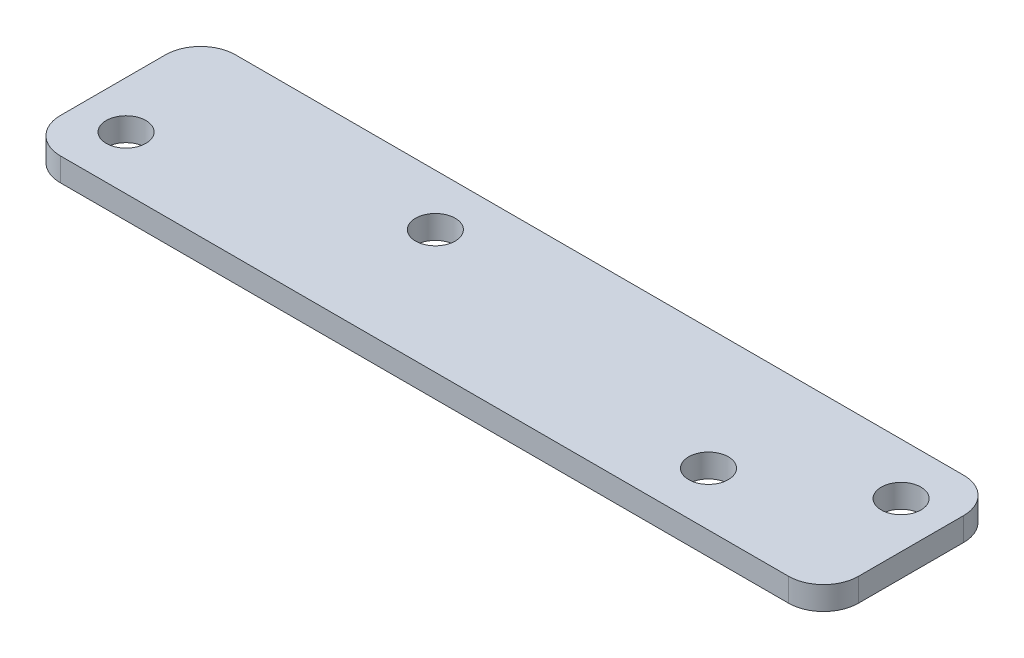
SolidWorks part; units mm, degrees
ref_plane "前视基准面" through (0, 0, 0) normal (0, 0, 1) x (1, 0, 0)
ref_plane "上视基准面" through (0, 0, 0) normal (0, 1, 0) x (1, 0, 0)
ref_plane "右视基准面" through (0, 0, 0) normal (1, 0, 0) x (0, 0, -1)
other "Configuration Table"
sketch "草图1" plane through (0, 0, 0) normal (0, 1, 0) x (1, 0, 0)
  line L1 (-107.5574, -1.3464) -> (-45.1803, -1.3464)
  line L2 (-110.5574, -4.3464) -> (-110.5574, -13.3464)
  line L3 (-107.5574, -16.3464) -> (-45.1803, -16.3464)
  line L4 (-42.1803, -4.3464) -> (-42.1803, -13.3464)
  circle A0 centre (-86.0228, -5.7574) radius 1.7
  circle A1 centre (-46.1228, -5.7574) radius 1.7
  circle A2 centre (-106.5228, -11.7574) radius 1.7
  circle A3 centre (-56.6228, -11.7574) radius 1.7
  arc A4 (-45.1803, -16.3464) -> (-42.1803, -13.3464) centre (-45.1803, -13.3464) ccw
  arc A5 (-45.1803, -1.3464) -> (-42.1803, -4.3464) centre (-45.1803, -4.3464) cw
  arc A6 (-110.5574, -13.3464) -> (-107.5574, -16.3464) centre (-107.5574, -13.3464) ccw
  arc A7 (-107.5574, -1.3464) -> (-110.5574, -4.3464) centre (-107.5574, -4.3464) ccw
  dimension "D1" = 39.9
  dimension "D2" = 49.9
  dimension "D5" = 3
  dimension "D3" = 10.5
  dimension "D4" = 6
extrude "凸台-拉伸1" add sketch "草图1" along normal blind 2
